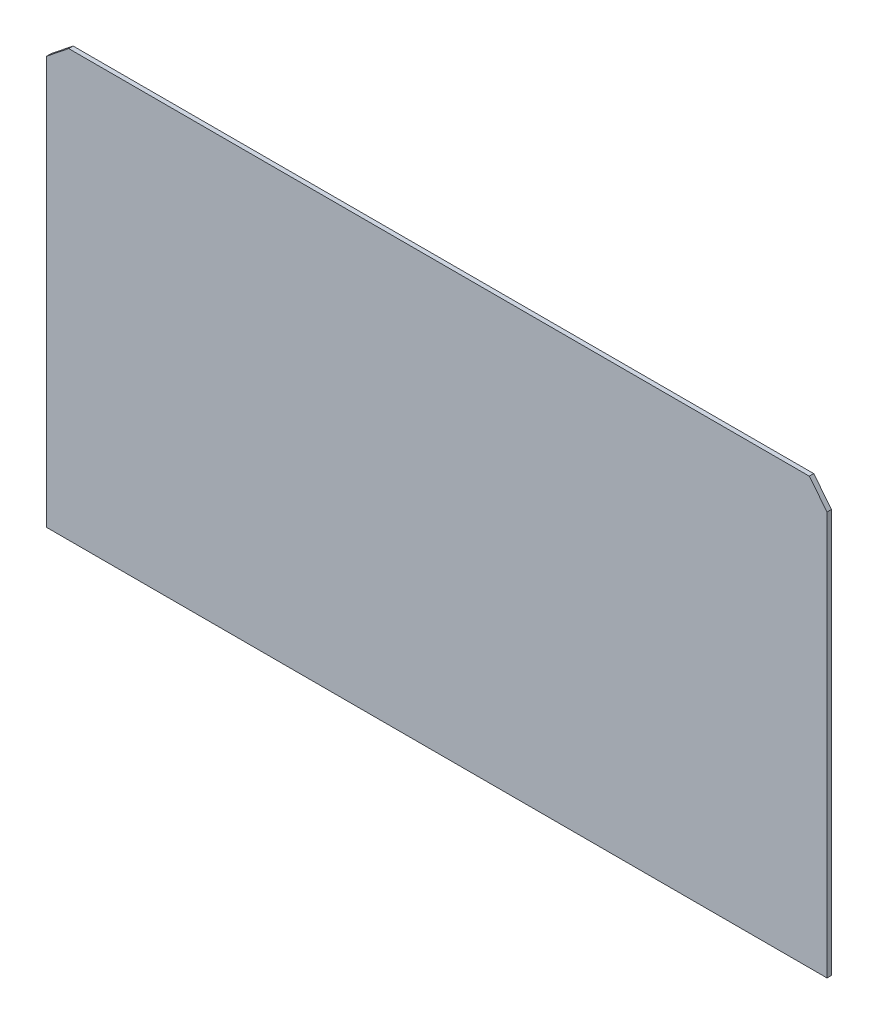
SolidWorks part; units mm, degrees
ref_plane "Front Plane" through (0, 0, 0) normal (0, 0, 1) x (1, 0, 0)
ref_plane "Top Plane" through (0, 0, 0) normal (0, 1, 0) x (1, 0, 0)
ref_plane "Right Plane" through (0, 0, 0) normal (1, 0, 0) x (0, 0, -1)
sketch "Sketch1" plane through (0, 0, 0) normal (0, 0, 1) x (1, 0, 0)
  line L1 (0, 0) -> (558.8, 0)
  line L2 (0, 0) -> (0, 304.8)
  line L3 (0, 304.8) -> (558.8, 304.8)
  line L4 (558.8, 0) -> (558.8, 304.8)
  dimension "D1" = 558.8
  dimension "D2" = 304.8
extrude "Boss-Extrude1" add sketch "Sketch1" along normal blind 3.175
chamfer "Chamfer1" distance 15.875 distance2 12.7 2 edges at (0, 304.8, 1.5875) (558.8, 304.8, 1.5875)
